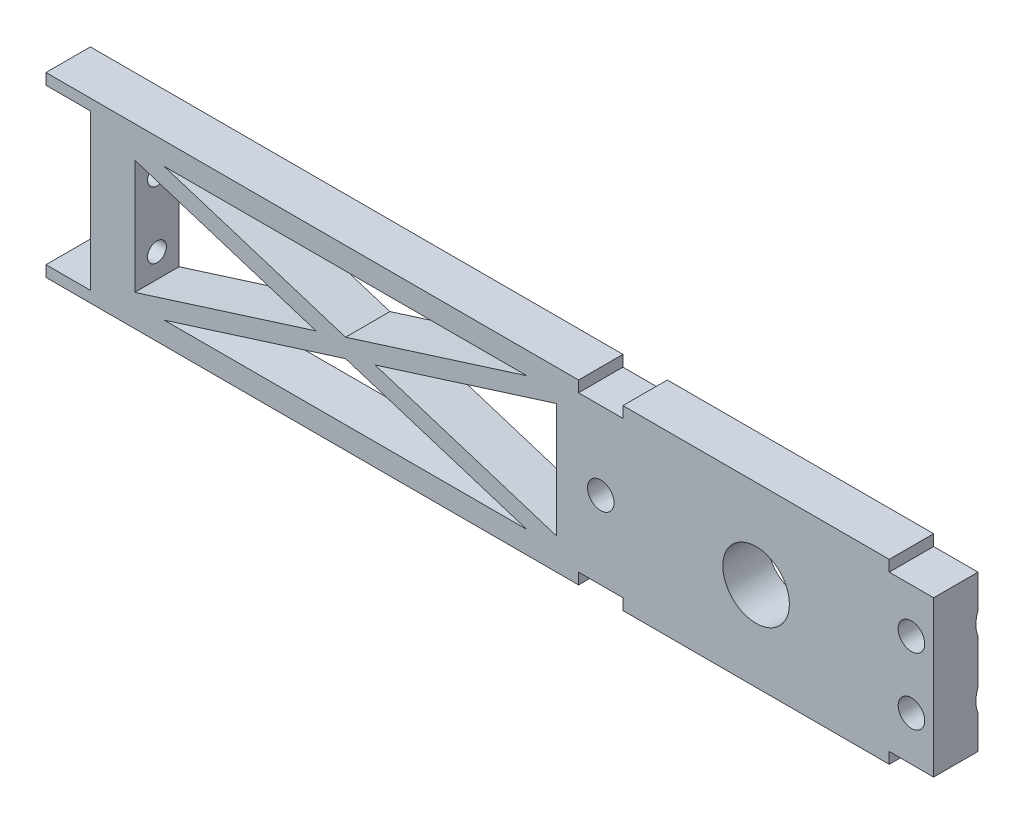
SolidWorks part; units mm, degrees
material "6061-T6 (SS)"
ref_plane "Front Plane" through (0, 0, 0) normal (0, 0, 1) x (1, 0, 0)
ref_plane "Top Plane" through (0, 0, 0) normal (0, 1, 0) x (1, 0, 0)
ref_plane "Right Plane" through (0, 0, 0) normal (1, 0, 0) x (0, 0, -1)
sketch "Sketch1" plane through (0, 0, 0) normal (0, 0, 1) x (1, 0, 0)
  line L0 (-89.2824, 8.314) -> (-28.9574, -10.736)
  line L1 (25.4, -12.7) -> (-101.6, -12.7)
  line L2 (25.4, -12.7) -> (25.4, 12.7)
  line L3 (25.4, 12.7) -> (-101.6, 12.7)
  line L4 (-101.6, -12.7) -> (-101.6, 12.7)
  line L5 (-88.9, 9.525) -> (-28.575, 9.525)
  line L6 (-88.9, 9.525) -> (-88.9, -9.525)
  line L7 (-88.9, -9.525) -> (-28.575, -9.525)
  line L8 (-28.575, 9.525) -> (-28.575, -9.525)
  line L9 (-88.9, 9.525) -> (-28.575, -9.525) construction
  line L10 (-88.9, -9.525) -> (-28.575, 9.525) construction
  line L17 (-88.5176, -10.736) -> (-28.1926, 8.314)
  line L18 (-88.5176, 10.736) -> (-28.1926, -8.314)
  line L19 (-89.2824, -8.314) -> (-28.9574, 10.736)
  circle A0 centre (0, 0) radius 4.7625
  arc A1 (-89.2824, 8.314) -> (-88.5176, 10.736) centre (-88.9, 9.525) cw
  arc A2 (-28.9574, -10.736) -> (-28.1926, -8.314) centre (-28.575, -9.525) ccw
  arc A3 (-88.5176, -10.736) -> (-89.2824, -8.314) centre (-88.9, -9.525) cw
  arc A4 (-28.1926, 8.314) -> (-28.9574, 10.736) centre (-28.575, 9.525) ccw
  point P7 (-58.7375, 0)
  dimension "D1" = 9.525
  dimension "D2" = 25.4
  dimension "D3" = 25.4
  dimension "D4" = 12.7
  dimension "D5" = 127
  dimension "D6" = 3.175
  dimension "D7" = 3.175
  dimension "D8" = 28.575
  dimension "D9" = 12.7
  dimension "D14" = 1.27
  dimension "D15" = 1.27
extrude "Boss-Extrude1" add sketch "Sketch1" along normal blind 6.35
hole_wizard "CSK for #6 Flat Head Machine Screw (100)1" positions "Sketch3" profile "Sketch4" countersink size "#6" standard "ANSI Inch" end condition through all
sketch "Sketch3" plane through (0, 0, 0) normal (0, 0, -1) x (-1, 0, 0)
  line L0 (-25.4, -12.7) -> (-25.4, 12.7) construction
  line L1 (-25.4, 12.7) -> (101.6, 12.7) construction
  line L2 (-25.4, -12.7) -> (101.6, -12.7) construction
  point P0 (-22.225, 4.7625)
  point P2 (-22.225, -4.7625)
  point P21 (22.225, 0)
  point P26 (-25.4, 0)
  dimension "D1" = 3.175
  dimension "D2" = 7.9375
  dimension "D3" = 7.9375
  dimension "D5" = 22.225
sketch "Sketch4" plane through (22.225, 4.7625, 0) normal (1, 0, 0) x (0, 1, 0)
  line L0 (0, 0) -> (0, 6.35)
  line L1 (0, 6.35) -> (1.8986, 6.35)
  line L2 (1.8986, 6.35) -> (1.8986, 1.38)
  line L3 (1.8986, 1.38) -> (3.5433, 0)
  line L5 (3.5433, 0) -> (0, 0)
  line L6 (-1.8987, 1.38) -> (-3.5433, 0) construction
  line L11 (0, -6.35) -> (0, 107.95) construction
  dimension "Thru Hole Dia." = 3.7973
  dimension "Thru Hole Depth" = 6.35
  dimension "Near C'Sink Dia." = 7.0866
  dimension "Near C'Sink Angle" = 100
ref_plane "Plane1" through (-38.1, 0, 0) normal (-1, 0, 0) x (0, 0, 1)
ref_plane "Plane2" through (0, 0, 0) normal (0, -1, 0) x (-1, 0, 0)
sketch "Sketch5" plane through (0, 0, 0) normal (0, 0, -1) x (-1, 0, 0)
  line L0 (101.6, -12.7) -> (101.6, 12.7) construction
  line L1 (-25.4, -12.7) -> (101.6, -12.7) construction
  line L3 (101.6, -11.1125) -> (95.25, -11.1125)
  line L5 (95.25, -11.1125) -> (101.6, -11.1125)
  line L6 (95.25, -11.1125) -> (95.25, 11.1125)
  line L7 (95.25, 11.1125) -> (101.6, 11.1125)
  line L8 (101.6, -11.1125) -> (101.6, 11.1125)
  line L9 (-25.4, 12.7) -> (101.6, 12.7) construction
  line M36 (101.6, -12.7) -> (101.6, 12.7)
  dimension "D1" = 1.5875
  dimension "D2" = 6.35
  dimension "D3" = 1.5875
extrude "Cut-Extrude1" cut sketch "Sketch5" against normal through all contours L7 L6 L3 M36
sketch "Sketch6" plane through (0, 0, 0) normal (0, 0, -1) x (-1, 0, 0)
  line L0 (-25.4, 12.7) -> (101.6, 12.7) construction
  line L1 (19.05, 12.7) -> (25.4, 12.7)
  line L2 (19.05, 12.7) -> (19.05, 11.1125)
  line L3 (19.05, 11.1125) -> (25.4, 11.1125)
  line L4 (25.4, 12.7) -> (25.4, 11.1125)
  line L7 (-25.4, 12.7) -> (-19.05, 12.7)
  line L8 (-25.4, 12.7) -> (-25.4, 11.1125)
  line L9 (-25.4, 11.1125) -> (-19.05, 11.1125)
  line L10 (-19.05, 12.7) -> (-19.05, 11.1125)
  dimension "D1" = 6.35
  dimension "D2" = 19.05
  dimension "D3" = 6.35
  dimension "D4" = 1.5875
extrude "Cut-Extrude2" cut sketch "Sketch6" against normal through all
mirror "Mirror3" about plane through (0, 0, 0) normal (0, -1, 0) of "Cut-Extrude2"
hole_wizard "Tap Drill for #6-32 Tap1" positions "Sketch8" profile "Sketch7" hole size "#6-32" standard "ANSI Inch"
sketch "Sketch8" plane through (-95.25, 0, 0) normal (-1, 0, 0) x (0, 0, 1)
  line L0 (6.35, 11.1125) -> (0, 11.1125) construction
  point P0 (3.175, 4.7625)
  point P2 (3.175, -4.7625)
  point P9 (3.175, 11.1125)
  dimension "D1" = 7.9375
  dimension "D2" = 7.9375
sketch "Sketch7" plane through (-95.25, 4.7625, 3.175) normal (0, 1, 0) x (0, 0, 1)
  line L0 (0, 0) -> (0, 7.1627)
  line L1 (0, 7.1627) -> (1.3525, 6.35)
  line L2 (1.3525, 6.35) -> (1.3525, 0)
  line L5 (1.3525, 0) -> (0, 0)
  line L10 (0, 7.1627) -> (-1.3525, 6.35) construction
  line L11 (0, -6.35) -> (0, 107.95) construction
  dimension "Hole Dia." = 2.7051
  dimension "Hole Depth" = 6.35
  dimension "Drill Angle" = 118
equation "\"D4@Sketch1\"=\"D3@Sketch1\"/2"
equation "\"D7@Sketch1\"=\"D6@Sketch1\""
equation "\"D3@Sketch3\" = \"D2@Sketch3\""
equation "\"Length\"= 5"
equation "\"Width\"= 5"
equation "\"D5@Sketch1\"=\"Length\""
